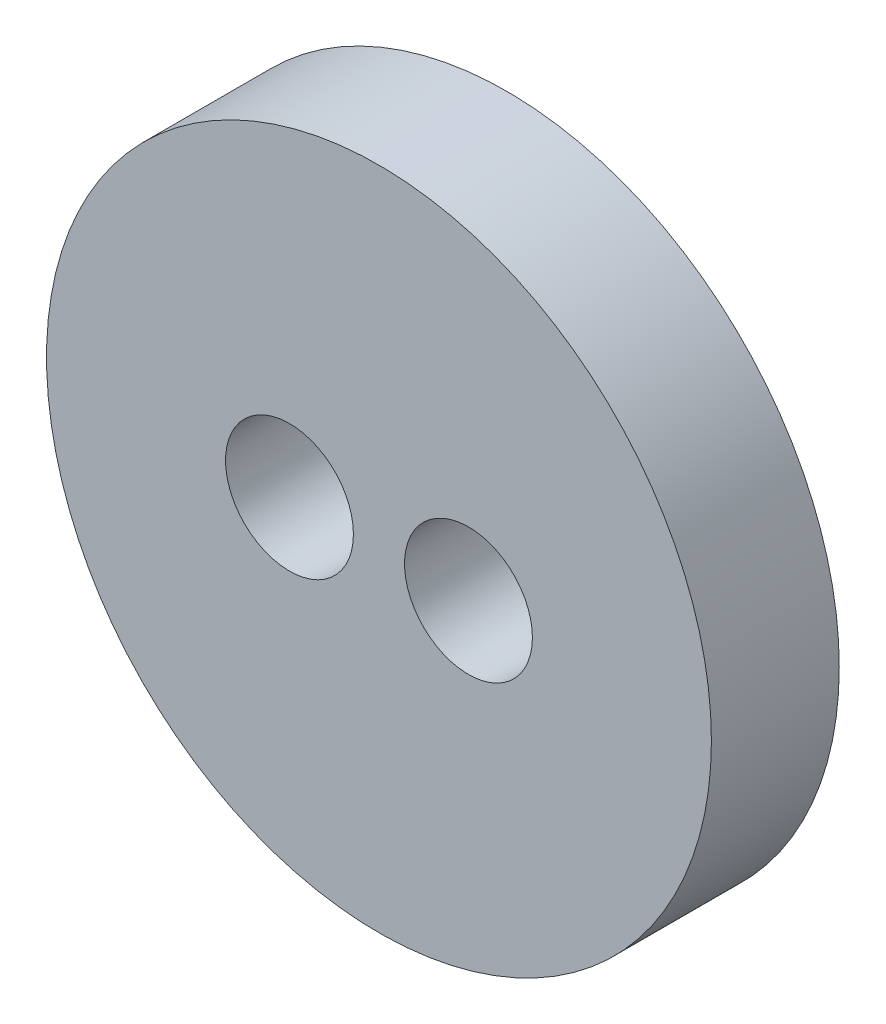
SolidWorks part; units mm, degrees
material "ABS"
ref_plane "Front Plane" through (0, 0, 0) normal (0, 0, 1) x (1, 0, 0)
ref_plane "Top Plane" through (0, 0, 0) normal (0, 1, 0) x (1, 0, 0)
ref_plane "Right Plane" through (0, 0, 0) normal (1, 0, 0) x (0, 0, -1)
sketch "Sketch1" plane through (0, 0, 0) normal (0, 0, 1) x (1, 0, 0)
  line L0 (-1.4, 0) -> (1.4, 0) construction
  circle A0 centre (0, 0) radius 3.2 construction
  circle A1 centre (1.4, 0) radius 1
  circle A2 centre (-1.4, 0) radius 1
  circle A3 centre (0, 0) radius 5.2
  point P8 (0, 0)
  dimension "Hole Diamater" = 2
  dimension "Hole Pair Gap" = 0.8
  dimension "Hole Edge to Joint" = 0.8
  dimension "Joint OD to Flange" = 2
extrude "Boss-Extrude1" add sketch "Sketch1" along normal blind 2
